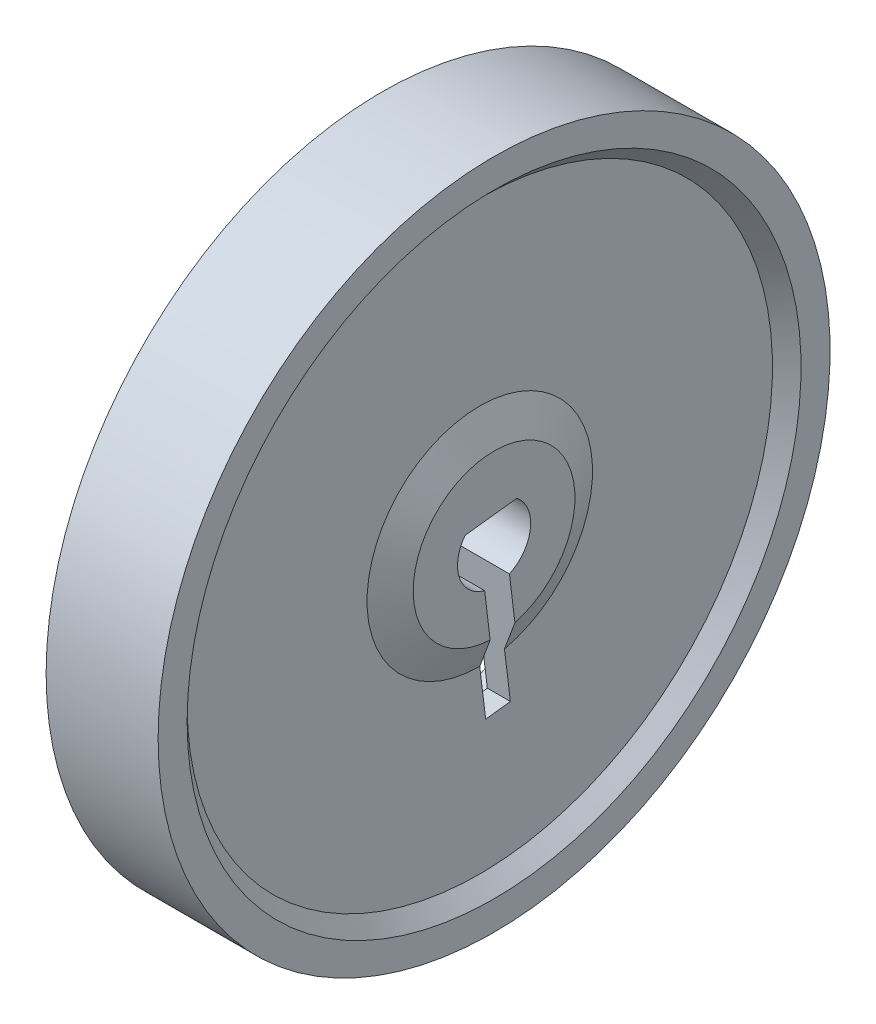
SolidWorks part; units mm, degrees
material "ABS"
ref_plane "Alzado" through (0, 0, 0) normal (0, 0, 1) x (1, 0, 0)
ref_plane "Planta" through (0, 0, 0) normal (0, 1, 0) x (1, 0, 0)
ref_plane "Vista lateral" through (0, 0, 0) normal (1, 0, 0) x (0, 0, -1)
sketch "Croquis1" plane through (0, 0, 0) normal (0, 0, 1) x (1, 0, 0)
  line L0 (0, 12.3341) -> (0, 13.5)
  line L1 (0, 13.5) -> (-4.5, 13.5)
  line L2 (-4.5, 13.5) -> (-4.5, 9.5835)
  line L3 (-4.5, 9.5835) -> (-1.5, 9.5835)
  line L4 (-1.5, 9.5835) -> (-1.5, 3.25)
  line L5 (-1.5, 3.25) -> (-7, 3.25)
  line L6 (-7, 3.25) -> (-7, 0)
  line L9 (0, 3.25) -> (0, 0)
  line L11 (-7, 0) -> (0, 0)
  line L13 (0, 12.3341) -> (-0.5749, 11.7592)
  line L14 (-0.5749, 11.7592) -> (-0.5749, 4.5303)
  line L15 (-0.5749, 4.5303) -> (0, 3.25)
  dimension "D1" = 3.25
  dimension "D2" = 7
  dimension "D3" = 4.5
  dimension "D5" = 13.5
  dimension "D7" = 1.5
revolve "Revolución2" add sketch "Croquis1" angle 360 about L11
sketch "Croquis2" plane through (0, 0, 0) normal (1, 0, 0) x (0, 0, -1)
  line L0 (0.9168, 1.1491) -> (0.5247, 1.1014) construction
  line L1 (0.5247, 1.1014) -> (-0.7734, 0.9436) construction
  line L2 (-0.7734, 0.9436) -> (-1.1655, 0.8959) construction
  line L3 (0.9168, 1.1491) -> (0.5247, 1.1014)
  line L4 (0.5247, 1.1014) -> (-0.7734, 0.9436)
  line L5 (-0.7734, 0.9436) -> (-1.1655, 0.8959)
  line L6 (-0.3802, -1.42) -> (0.2361, -6.4889)
  line L7 (0.2361, -6.4889) -> (1.2288, -6.3682)
  line L8 (1.2288, -6.3682) -> (0.6168, -1.3344)
  arc A0 (-1.1655, 0.8959) -> (0.9168, 1.1491) centre (0, 0) ccw construction
  arc A1 (-1.1655, 0.8959) -> (-0.3802, -1.42) centre (0, 0) ccw
  arc A2 (0.6168, -1.3344) -> (0.9168, 1.1491) centre (0, 0) ccw
  dimension "D1" = 1
  dimension "D2" = 0.5
  dimension "D4" = 7.5
extrude "Cortar-Extruir1" cut sketch "Croquis2" against normal blind 10
